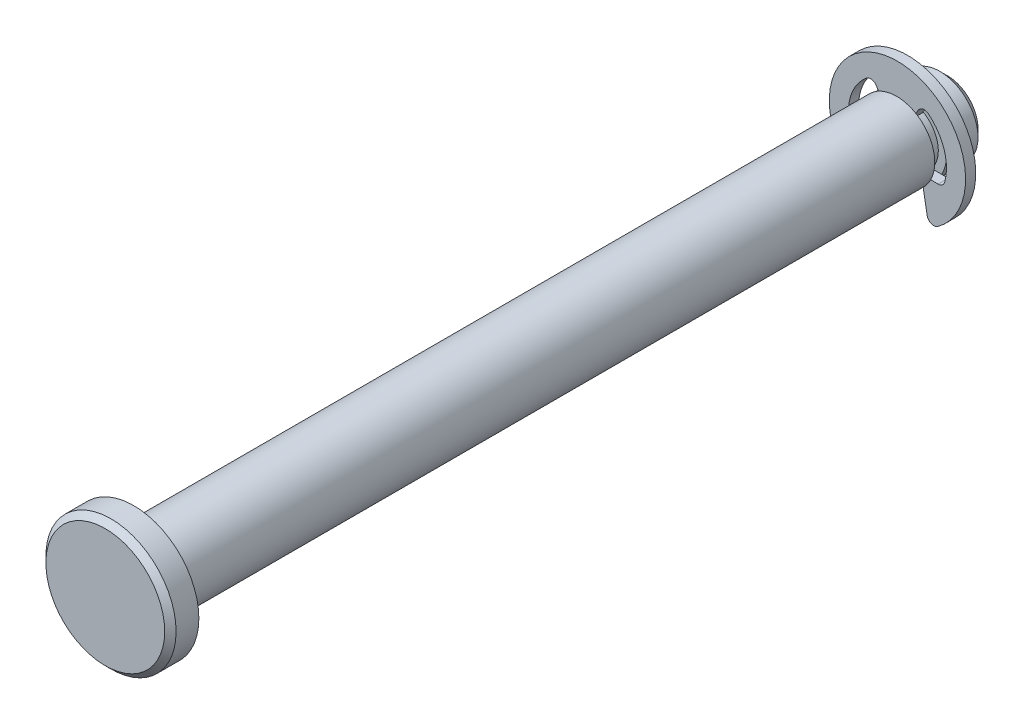
SolidWorks part; units mm, degrees
material "AISI Type 316L stainless steel"
ref_plane "Front" through (0, 0, 0) normal (0, 0, 1) x (1, 0, 0)
ref_plane "Top" through (0, 0, 0) normal (0, 1, 0) x (1, 0, 0)
ref_plane "Right" through (0, 0, 0) normal (1, 0, 0) x (0, 0, -1)
sketch "Sketch2" plane through (0, 0, 0) normal (0, 0, 1) x (1, 0, 0)
  circle A0 centre (0, 0) radius 2.3813
  point P3 (0, 2.3813)
  point P4 (0, -2.3813)
  dimension "dia" = 4.7625
extrude "Extrude1" add sketch "Sketch2" along normal mid plane 50.8
sketch "Sketch3" plane through (0, 0, 0) normal (1, 0, 0) x (0, 0, -1)
  line L0 (25.4, 2.3813) -> (-25.4, 2.3813) construction
  line L1 (22.225, 2.3813) -> (22.9616, 2.3813)
  line L2 (22.225, 2.3813) -> (22.225, 1.8669)
  line L3 (22.225, 1.8669) -> (22.9616, 1.8669)
  line L4 (22.9616, 2.3813) -> (22.9616, 1.8669)
  line L5 (-25.4, 2.3813) -> (-25.4, -2.3813) construction
  line L10 (22.9616, 1.8669) -> (22.9616, -1.8669) construction
  point P11 (22.9616, 0)
  point P14 (22.5933, 2.3813)
  dimension "groove wd" = 0.7366
  dimension "groove dia" = 3.7338
  dimension "usable lg" = 47.625
revolve "Cut-Revolve1" cut sketch "Sketch3" angle 360 about axis through (0, 0, 25.4) along (0, 0, -1)
sketch "Sketch8" plane through (0, 0, 25.4) normal (0, 0, 1) x (1, 0, 0)
  circle A0 centre (0, 0) radius 4.064
  dimension "head dia" = 8.128
extrude "Extrude6" add sketch "Sketch8" along normal blind 1.778
chamfer "Chamfer2" distance 0.3556 angle 45 1 edges at (4.064, 0, 27.178)
ref_plane "Plane1" through (0, 0, -22.5933) normal (0, 0, 1) x (1, 0, 0)
sketch "Sketch4" plane through (0, 0, -22.5933) normal (0, 0, 1) x (1, 0, 0)
  line L0 (0, 1.8669) -> (0, -1.8669) construction
  circle A0 centre (0, 0) radius 4.2545
  circle A1 centre (0, 0) radius 1.8669
  dimension "ring dia" = 8.509
extrude "Extrude2" add sketch "Sketch4" along normal mid plane 0.635 separate body
sketch "Sketch5" plane through (0, 0, 0) normal (0, 0, 1) x (1, 0, 0)
  line L0 (0, 4.2545) -> (0, 1.8669) construction
  line L1 (-1.5304, 2.6506) -> (0, 0)
  line L2 (-2.8484, -1.1201) -> (-1.4935, -1.1201)
  line L3 (0, 0) -> (1.5304, 2.6506)
  line L4 (-1.4935, -1.1201) -> (-1.9617, -3.7753)
  line L5 (1.4935, -1.1201) -> (1.9617, -3.7753)
  line L6 (1.4935, -1.1201) -> (2.8484, -1.1201)
  arc A0 (-1.5304, 2.6506) -> (-2.8484, -1.1201) centre (0, 0) ccw
  circle A1 centre (0, 0) radius 4.2545 construction
  circle A2 centre (0, 0) radius 1.8669 construction
  arc A3 (2.8484, -1.1201) -> (1.5304, 2.6506) centre (0, 0) ccw
  arc A4 (-1.9617, -3.7753) -> (1.9617, -3.7753) centre (0, 0) ccw
  circle A5 centre (0, 0) radius 1.8669 construction
  point P10 (0, 3.0607)
  dimension "D1" = 30
  dimension "D2" = 10
  dimension "D3" = 1.1201
extrude "Extrude4" cut sketch "Sketch5" against normal through all
sketch "Sketch6" plane through (0, 0, -22.2758) normal (0, 0, 1) x (1, 0, 0)
  line L0 (-0.9335, 1.6168) -> (0.9335, 1.6168)
  circle A0 centre (0, 0) radius 1.8669 construction
  arc A1 (0.9335, 1.6168) -> (-0.9335, 1.6168) centre (0, 0) ccw
extrude "Extrude5" add sketch "Sketch6" against normal up to surface (0.635 mm away) up to face at (0, 0.5273, -22.9108)
fillet "Fillet1" radius 0.4254 6 edges at (1.9617, -3.7753, -22.5933) (-1.9617, -3.7753, -22.5933) (2.8484, -1.1201, -22.5933) (1.5304, 2.6506, -22.5933) (-1.5304, 2.6506, -22.5933) (-2.8484, -1.1201, -22.5933)
chamfer "Chamfer1" distance 0.4763 angle 45 1 edges at (2.3813, 0, -25.4)
sketch "Sketch7" plane through (0, 0, 0) normal (1, 0, 0) x (0, 0, -1)
  line L0 (22.9108, 4.2545) -> (22.2758, 4.2545) construction
  line L1 (25.4, -2.3813) -> (25.4, 2.3813) construction
  line L2 (22.2758, -3.5079) -> (22.9108, -3.5079) construction
  line L3 (-27.178, 3.7084) -> (-27.178, -3.7084) construction
  point P0 (22.9616, -3.5079)
  point P1 (25.4, 2.3813)
  point P2 (-27.178, 4.064)
  point P6 (22.225, 4.2545)
  point P7 (25.4, -2.3813)
  point P12 (-25.4, 4.064)
  point P16 (22.225, -3.5079)
equation "\"D1@Chamfer1\" = \"dia@Sketch2\" * .1"
equation "\"D1@Fillet1\" = \"ring dia@Sketch4\" * .05"
equation "\"D3@Sketch5\" = \"groove dia@Sketch3\" * .3"
equation "\"D1@Chamfer2\" = \"head ht@Extrude6\" * .2"
